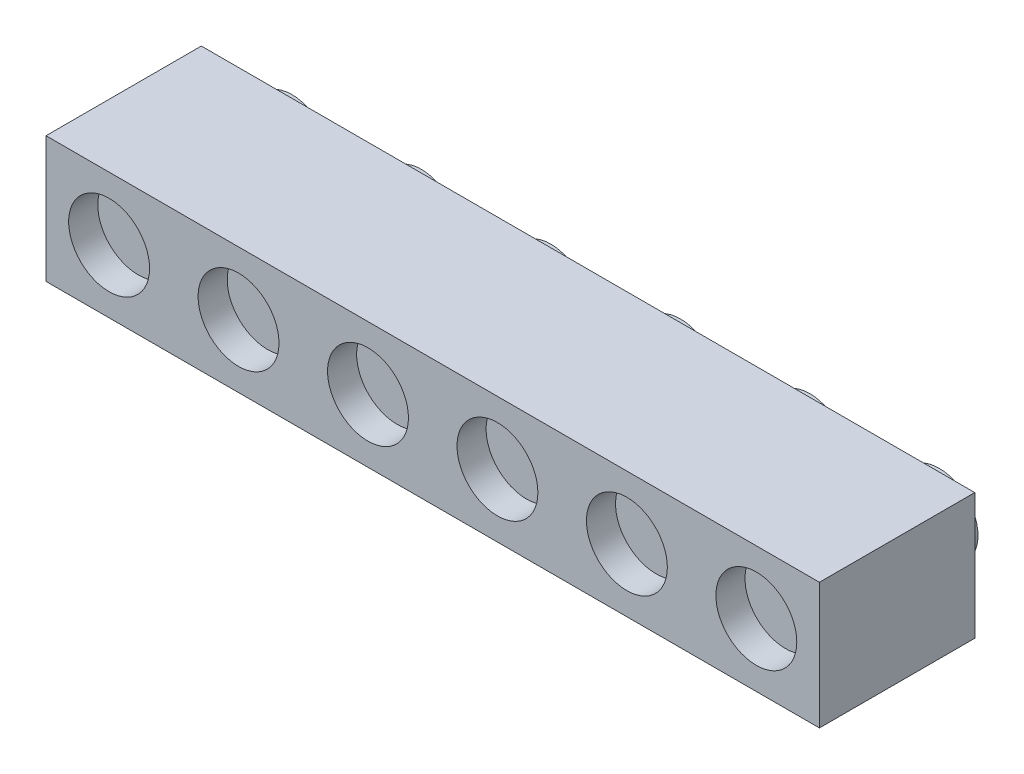
SolidWorks part; units mm, degrees
ref_plane "Спереди" through (0, 0, 0) normal (0, 0, 1) x (1, 0, 0)
ref_plane "Сверху" through (0, 0, 0) normal (0, 1, 0) x (1, 0, 0)
ref_plane "Справа" through (0, 0, 0) normal (1, 0, 0) x (0, 0, -1)
sketch "Эскиз1" plane through (0, 0, 0) normal (0, 0, 1) x (1, 0, 0)
  line L1 (23.9, -3.9) -> (-23.9, -3.9)
  line L2 (23.9, -3.9) -> (23.9, 3.9)
  line L3 (23.9, 3.9) -> (-23.9, 3.9)
  line L4 (-23.9, -3.9) -> (-23.9, 3.9)
  line L5 (23.9, -3.9) -> (-23.9, 3.9) construction
  line L6 (23.9, 3.9) -> (-23.9, -3.9) construction
  point P0 (0, 0)
  dimension "D1" = 7.8
  dimension "D2" = 47.8
extrude "Бобышка-Вытянуть1" add sketch "Эскиз1" along normal blind 9.6
sketch "Эскиз2" plane through (0, 0, 0) normal (0, 0, -1) x (-1, 0, 0)
  line L0 (-23.9, -3.9) -> (-23.9, 3.9) construction
  line L1 (-23.9, 3.9) -> (23.9, 3.9) construction
  circle A0 centre (-20, 0) radius 2.4
  circle A1 centre (-12, 0) radius 2.4
  circle A2 centre (-4, 0) radius 2.4
  circle A3 centre (4, 0) radius 2.4
  circle A4 centre (12, 0) radius 2.4
  circle A5 centre (20, 0) radius 2.4
  dimension "D1" = 3.9
  dimension "D2" = 3.9
  dimension "D3" = 6
extrude "Бобышка-Вытянуть2" add sketch "Эскиз2" along normal blind 1.7
sketch "Эскиз4" plane through (0, 0, 9.6) normal (0, 0, 1) x (1, 0, 0)
  line L0 (23.9, 3.9) -> (-23.9, 3.9) construction
  line L1 (-23.9, 3.9) -> (-23.9, -3.9) construction
  circle A0 centre (-20, 0) radius 2.5
  circle A1 centre (-12, 0) radius 2.5
  circle A2 centre (-4, 0) radius 2.5
  circle A3 centre (4, 0) radius 2.5
  circle A4 centre (12, 0) radius 2.5
  circle A5 centre (20, 0) radius 2.5
  dimension "D1" = 3.9
  dimension "D2" = 3.9
  dimension "D3" = 6
extrude "Вырез-Вытянуть1" cut sketch "Эскиз4" against normal blind 1.8
